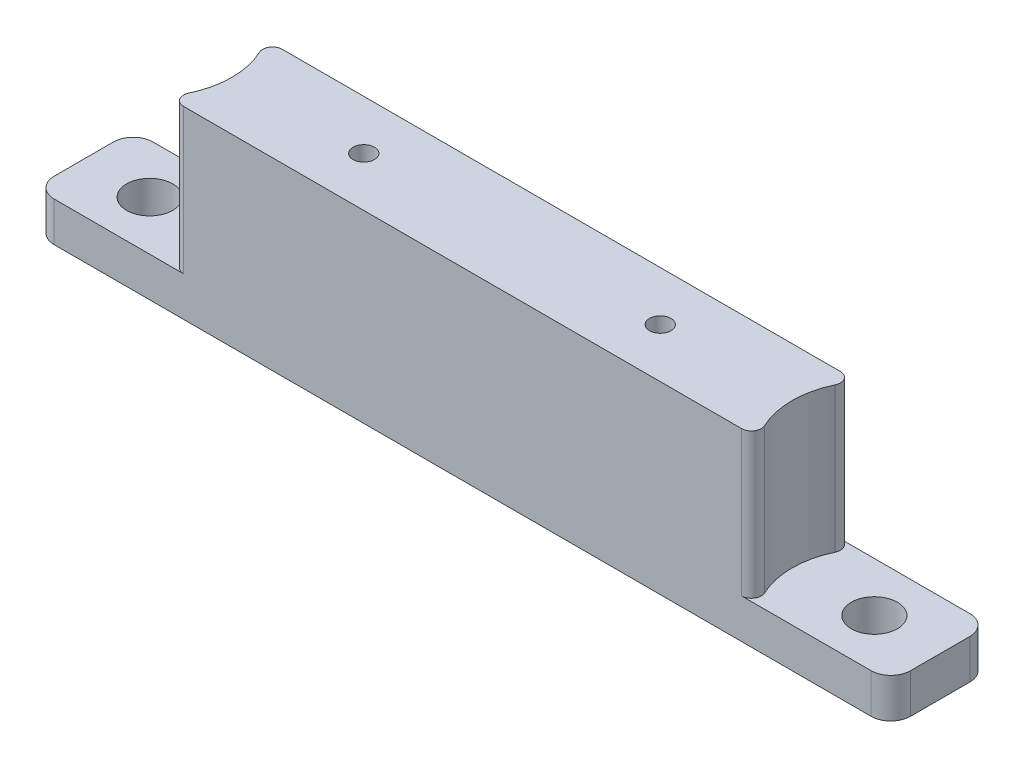
SolidWorks part; units mm, degrees
ref_plane "Front Plane" through (0, 0, 0) normal (0, 0, 1) x (1, 0, 0)
ref_plane "Top Plane" through (0, 0, 0) normal (0, 1, 0) x (1, 0, 0)
ref_plane "Right Plane" through (0, 0, 0) normal (1, 0, 0) x (0, 0, -1)
sketch "Sketch1" plane through (0, 0, 0) normal (0, 1, 0) x (1, 0, 0)
  line L1 (0, 0) -> (130, 0)
  line L2 (0, 0) -> (0, 15)
  line L3 (0, 15) -> (130, 15)
  line L4 (130, 0) -> (130, 15)
  dimension "D1" = 130
  dimension "D2" = 15
extrude "Boss-Extrude1" add sketch "Sketch1" along normal blind 6
sketch "Sketch2" plane through (0, 6, 0) normal (0, 1, 0) x (1, 0, 0)
  line L0 (130, 15) -> (0, 15) construction
  line L1 (20, 15) -> (110, 15)
  line L2 (20, 15) -> (20, 0)
  line L3 (20, 0) -> (110, 0)
  line L4 (110, 15) -> (110, 0)
  line L5 (0, 0) -> (130, 0) construction
  point P8 (65, 15)
  point P9 (65, 15)
  dimension "D1" = 90
extrude "Boss-Extrude2" add sketch "Sketch2" along normal blind 22
sketch "Sketch3" plane through (0, 6, 0) normal (0, 1, 0) x (1, 0, 0)
  line L0 (0, 15) -> (0, 0) construction
  line L1 (0, 0) -> (20, 0) construction
  line L2 (110, 0) -> (130, 0) construction
  line L3 (130, 0) -> (130, 15) construction
  circle A0 centre (10, 7.5) radius 3.5
  circle A1 centre (120, 7.5) radius 3.5
  point P5 (0, 7.5)
  point P9 (10, 0)
  point P12 (120, 0)
  point P15 (130, 7.5)
  dimension "D1" = 7
  dimension "D2" = 7
extrude "Cut-Extrude1" cut sketch "Sketch3" against normal up to next
sketch "Sketch4" plane through (0, 6, 0) normal (0, 1, 0) x (1, 0, 0)
  circle A0 centre (10, 7.5) radius 12.5
  circle A1 centre (120, 7.5) radius 12.5
  dimension "D1" = 25
  dimension "D2" = 25
extrude "Cut-Extrude2" cut sketch "Sketch4" along normal up to next
sketch "Sketch5" plane through (0, 28, 0) normal (0, 1, 0) x (1, 0, 0)
  line L0 (65, 15) -> (65, 0) construction
  line L1 (110, 15) -> (20, 15) construction
  line L2 (20, 0) -> (110, 0) construction
  circle A0 centre (42.5, 7.5) radius 1.625
  circle A1 centre (87.5, 7.5) radius 1.625
  point P10 (65, 15)
  point P11 (0, 0)
  point P12 (0, 0)
  point P13 (65, 7.5)
  dimension "D3" = 3.25
  dimension "D4" = 3.25
  dimension "D1" = 22.5
  dimension "D2" = 22.5
extrude "Cut-Extrude3" cut sketch "Sketch5" against normal up to next
sketch "Sketch6" plane through (0, 0, 0) normal (0, -1, 0) x (1, 0, 0)
  circle A0 centre (42.5, -7.5) radius 3.5
  circle A1 centre (87.5, -7.5) radius 3.5
  dimension "D1" = 7
  dimension "D2" = 7
extrude "Cut-Extrude4" cut sketch "Sketch6" against normal blind 25.5
fillet "Fillet1" radius 3 4 edges at (130, 3, -15) (130, 3, 0) (0, 3, -15) (0, 3, 0)
fillet "Fillet3" radius 1.5 4 edges at (110, 17, -15) (110, 17, 0) (20, 17, -15) (20, 17, 0)
